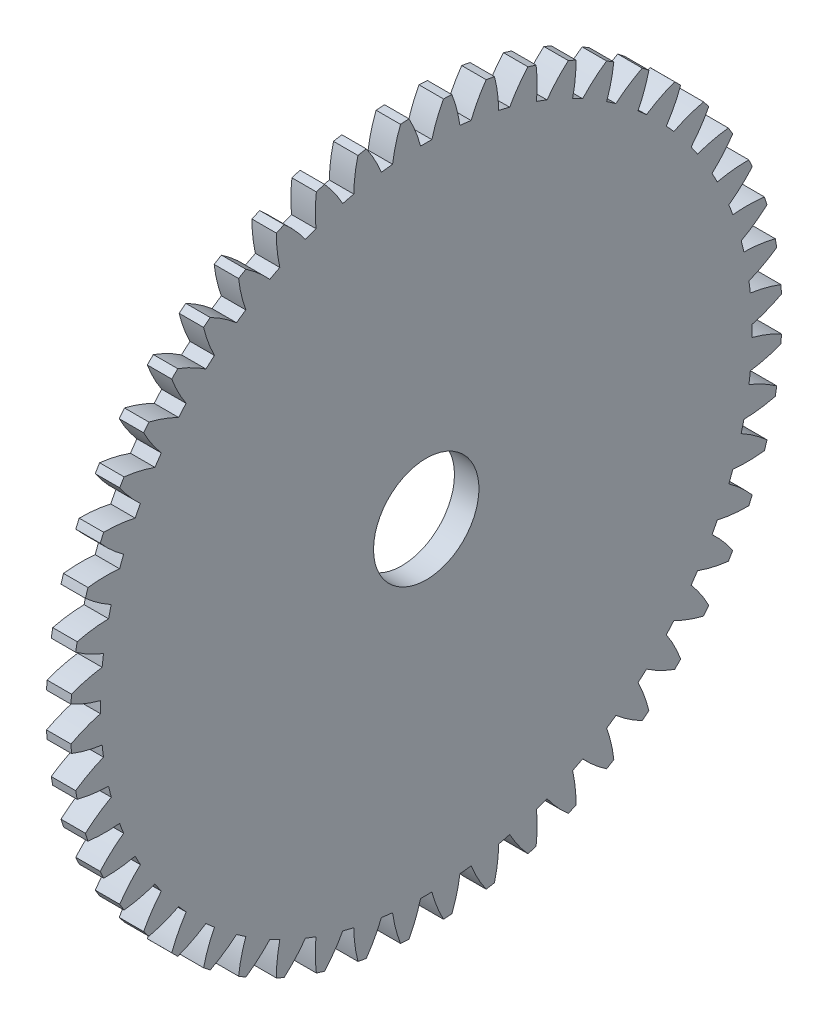
SolidWorks part; units mm, degrees
ref_plane "Plane1" through (0, 0, 0) normal (0, 0, 1) x (1, 0, 0)
ref_plane "Plane2" through (0, 0, 0) normal (0, 1, 0) x (1, 0, 0)
ref_plane "Plane3" through (0, 0, 0) normal (1, 0, 0) x (0, 0, -1)
other "Configuration Table"
sketch "HoldingSke" plane through (0, 0, 0) normal (0, 1, 0) x (1, 0, 0)
  line L0 (0, 0) -> (500.4096, -640.4951)
  line L1 (-15, 0) -> (100, 0) construction
  line L2 (0, 0) -> (-2.1039, 2.3779)
  line L3 (0, 0) -> (-11.863, 4.5341)
  line L4 (0, 0) -> (5.3169, 6.8053)
  line L5 (0, 0) -> (-47.5972, -17.7524)
  line L6 (0, 0) -> (-1.2212, -0.824)
  line L7 (-2.1039, 2.3779) -> (8.8308, 51.9871)
  line L8 (-76.2, 54.61) -> (-69.596, 54.61)
  line L9 (-71.009, 38.7566) -> (-53.1078, 45.2721)
  line L10 (-76.2, 71.12) -> (104.1128, 71.12)
  line L11 (0, 0) -> (-1.4732, 0)
  line L12 (-76.2, 101.6) -> (-76.1716, 101.6)
  line L13 (24.9733, 27.94) -> (52.9518, 28.4284)
  line L14 (24.9733, 27.94) -> (25.0241, 27.9398)
  line L15 (24.9733, 27.94) -> (100.4021, 29.52)
  circle A0 centre (0, 0) radius 3.175
  circle A1 centre (0, 0) radius 19.6342
  circle A2 centre (0, 0) radius 38.1
  circle A3 centre (0, 0) radius 3.175
  dimension "MHD" = 39.2684
  dimension "Hub_dia" = 76.2
  dimension "Bore" = 6.35
  dimension "MBD" = 6.35
  dimension "Num_teeth" = 52
  dimension "Pitch" = 812.8
  dimension "Overall_len" = 50.8
  dimension "Show_teeth" = 52
  dimension "Thickness" = 1.4732
  dimension "OAL" = 50.8001
  dimension "T_dim" = 6.604
  dimension "Ap" = 20
  dimension "H" = 19.05
  dimension "Pitch_radius" = 180.3128
  dimension "Width" = 1.4732
  dimension "Backlash" = 0.0284
  dimension "Addendum_fac" = 1
  dimension "Dedendum_fac" = 1.2
  dimension "Clearance_fac" = 0.2
  dimension "Dedendum_add" = 0.0508
sketch "BasProSke" plane through (0, 0, 0) normal (0, 1, 0) x (1, 0, 0)
  line L0 (-10, 0) -> (60, 0) construction
  line L1 (0, 0) -> (0, 21.4312)
  line L2 (0, 0) -> (1.4732, 0)
  line L3 (1.4732, 0) -> (1.4732, 21.4312)
  line L4 (1.4732, 21.4312) -> (0, 21.4312)
  dimension "Thickness" = 1.4732
  dimension "Diameter" = 42.8625
revolve "Base-Revolve" add sketch "BasProSke" angle 360 about L0
sketch "TooCutSke" plane through (0, 0, 0) normal (1, 0, 0) x (0, 0, -1)
  line L1 (0, 0) -> (0, 107) construction
  line L2 (0, 0) -> (-0.6731, 20.6265) construction
  line L3 (0, 0) -> (-2.4912, 41.1838) construction
  line L4 (-0.6731, 20.6265) -> (-1.2456, 20.5919) construction
  arc A0 (0.3404, 19.6312) -> (-0.3404, 19.6312) centre (0, 0) ccw
  arc A1 (1.0518, 21.4309) -> (-1.0518, 21.4309) centre (0, 0) ccw
  circle A2 centre (0, 0) radius 20.6375 construction
  circle A3 centre (0, 0) radius 19.3929 construction
  arc A4 (-0.3404, 19.6312) -> (-1.0518, 21.4309) centre (-8.3202, 17.5174) ccw
  arc A5 (1.0518, 21.4309) -> (0.3404, 19.6312) centre (8.3202, 17.5174) ccw
  dimension "Root_dia" = 39.2684
  dimension "Overcut_dia" = 42.9133
  dimension "Pitch_dia" = 41.275
  dimension "Base_dia" = 38.7858
  dimension "Flank_rad" = 8.255
  dimension "Half_ang" = 3.462
  dimension "Half_CT" = 0.5735
extrude "ToothCut" cut sketch "TooCutSke" along normal through all
fillet "Breaks" [suppressed] radius 0.0159
fillet "RootFillets" [suppressed] radius 0.2095
pattern_circular "TeethCuts" count 52 every 6.923 about axis through (-10, 0, 0) along (1, 0, 0) of "ToothCut"
sketch "HubNeaOneSke" plane through (0, 0, 0) normal (-1, 0, 0) x (0, 0, 1)
  circle A0 centre (0, 0) radius 19.6342
  dimension "Diameter" = 39.2684
extrude "HubNearOne" [suppressed] add sketch "HubNeaOneSke" along normal blind 49.3269
sketch "HubNeaBotSke" plane through (0, 0, 0) normal (-1, 0, 0) x (0, 0, 1)
  circle A0 centre (0, 0) radius 19.6342
  dimension "Diameter" = 39.2684
extrude "HubNearBoth" [suppressed] add sketch "HubNeaBotSke" along normal blind 24.6634
ref_plane "FarPln" through (1.4732, 0, 0) normal (1, 0, 0) x (0, 0, -1)
sketch "HubFarSke" plane through (1.4732, 0, 0) normal (1, 0, 0) x (0, 0, -1)
  circle A0 centre (0, 0) radius 19.6342
  dimension "Diameter" = 39.2684
extrude "HubFar" [suppressed] add sketch "HubFarSke" along normal blind 24.6634
sketch "BorSke" plane through (0, 0, 0) normal (1, 0, 0) x (0, 0, -1)
  circle A0 centre (0, 0) radius 3.175
  dimension "Diameter" = 6.35
extrude "Bore" cut sketch "BorSke" along normal mid plane 101.6001
sketch "KeySke" plane through (0, 0, 0) normal (1, 0, 0) x (0, 0, -1)
  line L0 (-0.127, 0) -> (-0.127, 3.429)
  line L1 (-0.127, 3.429) -> (0.127, 3.429)
  line L2 (0.127, 3.429) -> (0.127, 0)
  line L3 (0, 0) -> (0, 34) construction
  line L4 (-0.127, 0) -> (0.127, 0)
  dimension "Offset" = 3.429
  dimension "Width" = 0.254
extrude "Keyway" [suppressed] cut sketch "KeySke" along normal mid plane 101.6001
pattern_circular "Keyway2" [suppressed] count 2 every 90 about axis through (-10, 0, 0) along (1, 0, 0)
equation "' \"Pitch@HoldingSke\" = 4"
equation "' \"Num_teeth@HoldingSke\" = 12"
equation "' \"Ap@HoldingSke\" =  20"
equation "' \"Ap@HoldingSke\" = 20"
equation "' \"Width@HoldingSke\" = 0.5"
equation "' \"Hub_dia@HoldingSke\"= 1"
equation "' \"Hub_dia@HoldingSke\" = 1"
equation "' \"Overall_len@HoldingSke\" = 1.0"
equation "' \"Bore@HoldingSke\" = 0.75"
equation "' \"T_dim@HoldingSke\" = 0.85"
equation "' \"Width@KeySke\" = 0.25"
equation "' \"Show_teeth@HoldingSke\" = 13"
equation "' \"Backlash@HoldingSke\" = 0.009"
equation "' \"Addendum_fac@HoldingSke\" = 1.0"
equation "' \"Dedendum_fac@HoldingSke\" = 1.25"
equation "' \"Dedendum_add@HoldingSke\" = 0.00005"
equation "' \"Clearance_fac@HoldingSke\" = 0.25"
equation "' \"Pitch@HoldingSke\" = 0.5"
equation "' \"Num_teeth@HoldingSke\" = 23"
equation "' \"Show_teeth@HoldingSke\" = 23"
equation "' \"Backlash@HoldingSke\" = 0.0375"
equation "\"Overcut_dia@TooCutSke\" = (\"Num_teeth@HoldingSke\" + 2 * \"Addendum_fac@HoldingSke\") / \"Pitch@HoldingSke\" + 0.002"
equation "\"Pitch_dia@TooCutSke\" = \"Num_teeth@HoldingSke\" / \"Pitch@HoldingSke\""
equation "\"Base_dia@TooCutSke\" = \"Num_teeth@HoldingSke\" / \"Pitch@HoldingSke\" * cos((\"Ap@HoldingSke\"  * 3.14159265 / 180))"
equation "\"Root_dia@TooCutSke\" = (\"Num_teeth@HoldingSke\" + 2) / \"Pitch@HoldingSke\" - 2 * (\"Addendum_fac@HoldingSke\" + \"Dedendum_fac@HoldingSke\") / \"Pitch@HoldingSke\" - \"Dedendum_add@HoldingSke\" * 2"
equation "\"Half_ang@TooCutSke\" = 180 / \"Num_teeth@HoldingSke\""
equation "\"Half_CT@TooCutSke\" = \"Num_teeth@HoldingSke\" / \"Pitch@HoldingSke\" * sin((3.14159265 / 2 / \"Num_teeth@HoldingSke\")) / 2 - 7 * \"Backlash@HoldingSke\" / 4"
equation "\"Flank_rad@TooCutSke\" = \"Num_teeth@HoldingSke\" / \"Pitch@HoldingSke\" / 5"
equation "\"Radius@RootFillets\" = \"Clearance_fac@HoldingSke\" / \"Pitch@HoldingSke\" + \"Dedendum_add@HoldingSke\""
equation "\"Break_rad@Breaks\" = 0.02 / \"Pitch@HoldingSke\""
equation "\"Thickness@HoldingSke\" = \"Width@HoldingSke\""
equation "\"OAL@HoldingSke\" = \"Thickness@HoldingSke\""
equation "\"MHD@HoldingSke\" = (\"Num_teeth@HoldingSke\" + 2) / \"Pitch@HoldingSke\" - 2 * (\"Addendum_fac@HoldingSke\" + \"Dedendum_fac@HoldingSke\")  / \"Pitch@HoldingSke\" - \"Dedendum_add@HoldingSke\" * 2"
equation "\"MBD@HoldingSke\" = (\"Num_teeth@HoldingSke\" + 2) / \"Pitch@HoldingSke\" - 2 * (\"Addendum_fac@HoldingSke\" + \"Dedendum_fac@HoldingSke\")  / \"Pitch@HoldingSke\" - \"Dedendum_add@HoldingSke\" * 2 - 0.002"
equation "\"MHD@HoldingSke\" = ((sgn( \"MHD@HoldingSke\" - \"Hub_dia@HoldingSke\" )-1)*( \"MHD@HoldingSke\" - \"Hub_dia@HoldingSke\" ))/-2+ \"Hub_dia@HoldingSke\""
equation "\"MBD@HoldingSke\" = ((sgn( \"MBD@HoldingSke\" - \"Bore@HoldingSke\" )-1)*( \"MBD@HoldingSke\" - \"Bore@HoldingSke\" ))/-2+ \"Bore@HoldingSke\""
equation "\"OAL@HoldingSke\" = ((sgn( \"OAL@HoldingSke\" - \"Overall_len@HoldingSke\" )+1)*( \"OAL@HoldingSke\" - \"Overall_len@HoldingSke\" ))/2 + \"Overall_len@HoldingSke\" + 0.000002"
equation "\"Num_teeth@TeethCuts\" = int( \"Show_teeth@HoldingSke\" ) + 1"
equation "\"Num_teeth@TeethCuts\" = ((sgn( \"Num_teeth@TeethCuts\" - \"Num_teeth@HoldingSke\" )-1)*( \"Num_teeth@TeethCuts\" - \"Num_teeth@HoldingSke\" ))/-2+ \"Num_teeth@HoldingSke\""
equation "\"Num_teeth@TeethCuts\" = ((sgn( \"Num_teeth@TeethCuts\" - 2.0)+1)*( \"Num_teeth@TeethCuts\" - 2.0))/2 +2.0"
equation "\"Angle@TeethCuts\" = 360.0 / \"Num_teeth@HoldingSke\""
equation "\"Diameter@BasProSke\" = (\"Num_teeth@HoldingSke\" + 2 * \"Addendum_fac@HoldingSke\") / \"Pitch@HoldingSke\""
equation "\"Thickness@BasProSke\"  = \"Thickness@HoldingSke\""
equation "' \"Fillet_rad@BasProSke\" =  \"Thickness@HoldingSke\" * 0.05"
equation "' \"Fillet_rad@BasProSke\" = \"Thickness@HoldingSke\" * 0.05"
equation "\"MHD@HoldingSke\" = ((sgn( \"MHD@HoldingSke\" - \"Root_dia@TooCutSke\" )-1)*( \"MHD@HoldingSke\" - \"Root_dia@TooCutSke\" ))/-2+ \"Root_dia@TooCutSke\""
equation "\"Diameter@HubNeaOneSke\" = \"MHD@HoldingSke\""
equation "\"Length@HubNearOne\" = \"OAL@HoldingSke\" - \"Thickness@BasProSke\""
equation "\"Diameter@HubNeaBotSke\" = \"MHD@HoldingSke\""
equation "\"Length@HubNearBoth\" = ( \"OAL@HoldingSke\" - \"Thickness@BasProSke\" ) / 2.0"
equation "\"Thickness@FarPln\" = \"Thickness@BasProSke\""
equation "\"Diameter@HubFarSke\" = \"MHD@HoldingSke\""
equation "\"Length@HubFar\" = ( \"OAL@HoldingSke\" - \"Thickness@BasProSke\" ) / 2.0"
equation "\"Diameter@BorSke\" = \"MBD@HoldingSke\""
equation "\"D1@Bore\" = \"OAL@HoldingSke\" * 2.0"
equation "\"D1@Keyway\" = \"OAL@HoldingSke\" * 2.0"
equation "\"Offset@KeySke\" = \"T_dim@HoldingSke\" - \"MBD@HoldingSke\" / 2.0"
